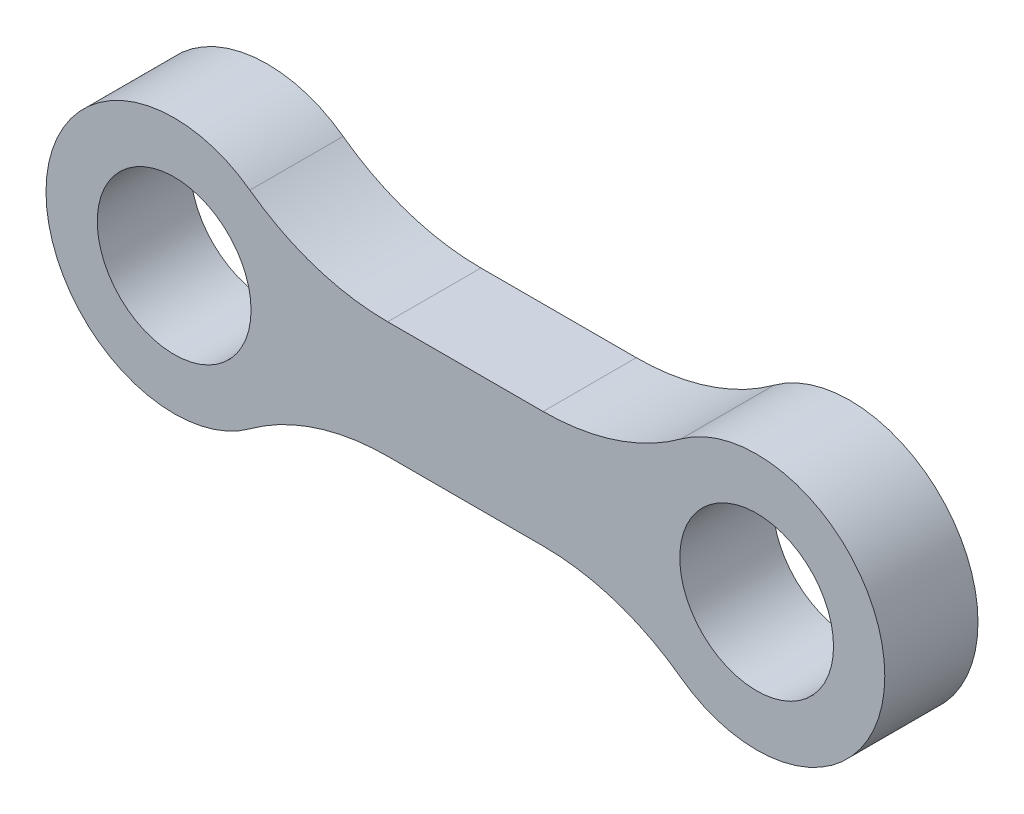
SolidWorks part; units mm, degrees
ref_plane "正面" through (0, 0, 0) normal (0, 0, 1) x (1, 0, 0)
ref_plane "平面" through (0, 0, 0) normal (0, 1, 0) x (1, 0, 0)
ref_plane "右側面" through (0, 0, 0) normal (1, 0, 0) x (0, 0, -1)
sketch "ｽｹｯﾁ1" plane through (0, 0, 0) normal (0, 0, 1) x (1, 0, 0)
  line L1 (0, 5) -> (-30, 5)
  line L2 (0, 5) -> (0, 0)
  line L3 (0, 0) -> (-30, 0)
  line L4 (-30, 5) -> (-30, 0)
  circle A2 centre (-27.5, 2.5) radius 3.3
  circle A3 centre (-27.5, 2.5) radius 5.5
  circle A4 centre (-2.5, 2.5) radius 3.3
  circle A5 centre (-2.5, 2.5) radius 5.5
  point P4 (-2.5, 2)
  dimension "D2" = 5
  dimension "D5" = 6.6
  dimension "D6" = 11
  dimension "D9" = 6.6
  dimension "D10" = 11
  dimension "D3" = 0
  dimension "D4" = 30
  dimension "D7" = 2.5
  dimension "D8" = 2.5
  dimension "D11" = 90
  dimension "D12" = 90
  dimension "D13" = 90
  dimension "D14" = 2.5
  dimension "D15" = 2.5
extrude "ﾎﾞｽ - 押し出し1" add sketch "ｽｹｯﾁ1" against normal blind 4 contours L3 A5 L1 A4 L2 | L1 A5 L3 A4 | A4 L3 L2 | A4 L2 L1 | A5 L1 A3 L3 | L3 A3 L1 A2 | L1 A3 L3 A2 L4 | A2 L1 L4 | A2 L4 L3
fillet "ﾌｨﾚｯﾄ1" radius 10 4 edges at (-7.399, 0, -2) (-22.601, 0, -2) (-7.399, 5, -2) (-22.601, 5, -2)
